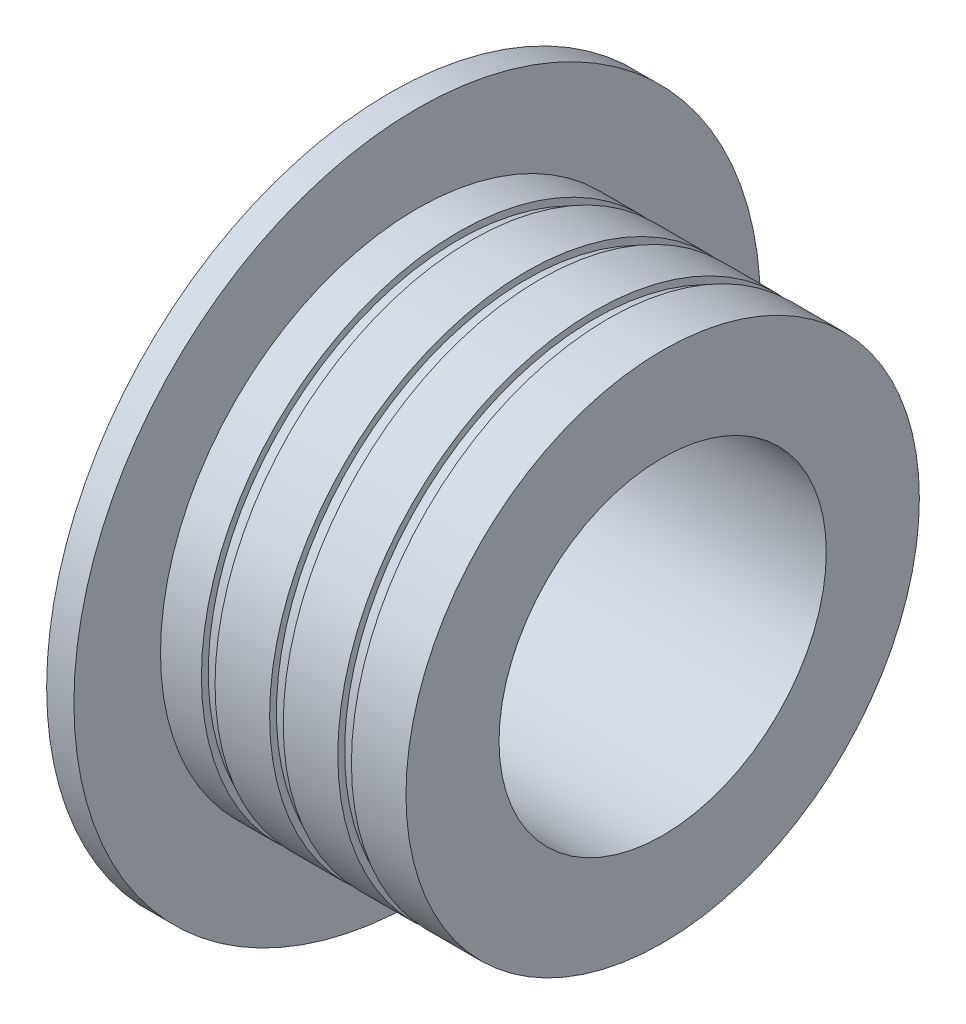
SolidWorks part; units mm, degrees
material "Galvanized Steel"
ref_plane "Front Plane" through (0, 0, 0) normal (0, 0, 1) x (1, 0, 0)
ref_plane "Top Plane" through (0, 0, 0) normal (0, 1, 0) x (1, 0, 0)
ref_plane "Right Plane" through (0, 0, 0) normal (1, 0, 0) x (0, 0, -1)
sketch "Sketch1" plane through (0, 0, 0) normal (0, 0, 1) x (1, 0, 0)
  line L0 (-7.2593, 9.2491) -> (-9.2593, 9.2491)
  line L1 (-9.2593, 9.2491) -> (-9.2593, -3.9259)
  line L2 (-9.2593, -15.9259) -> (10.7407, -15.9259)
  line L3 (10.7407, 2.8991) -> (10.7407, -3.9259)
  line L4 (10.7407, 2.8991) -> (-7.2593, 2.8991)
  line L5 (-7.2593, 9.2491) -> (-7.2593, 2.8991)
  line L6 (10.7407, -3.9259) -> (-9.2593, -3.9259)
  dimension "D1" = 2
  dimension "D2" = 12
  dimension "D3" = 20
revolve "Revolve1" add sketch "Sketch1" angle 360 about L2
sketch "Sketch2" plane through (0, 0, 0) normal (0, 0, 1) x (1, 0, 0)
  line L0 (10.7407, 2.8991) -> (-7.2593, 2.8991) construction
  line L1 (6.7407, 2.8991) -> (5.7407, 2.8991)
  line L2 (6.7407, 2.8991) -> (6.7407, 2.3991)
  line L3 (6.7407, 2.3991) -> (5.7407, 2.3991)
  line L4 (5.7407, 2.8991) -> (5.7407, 2.3991)
  line L5 (10.7407, -34.7509) -> (10.7407, 2.8991) construction
  line L6 (1.7407, 2.8991) -> (0.7407, 2.8991)
  line L7 (1.7407, 2.8991) -> (1.7407, 2.3991)
  line L8 (1.7407, 2.3991) -> (0.7407, 2.3991)
  line L9 (0.7407, 2.8991) -> (0.7407, 2.3991)
  line L10 (-3.2593, 2.8991) -> (-4.2593, 2.8991)
  line L11 (-3.2593, 2.8991) -> (-3.2593, 2.3991)
  line L12 (-3.2593, 2.3991) -> (-4.2593, 2.3991)
  line L13 (-4.2593, 2.8991) -> (-4.2593, 2.3991)
  line L14 (10.7407, -15.9259) -> (-12.0161, -15.9259)
  dimension "D1" = 0.5
  dimension "D2" = 1
  dimension "D3" = 0.5
  dimension "D4" = 1
  dimension "D5" = 0.5
  dimension "D6" = 1
  dimension "D7" = 4
  dimension "D8" = 4
  dimension "D9" = 4
revolve "Cut-Revolve1" cut sketch "Sketch2" angle 360 about L14
